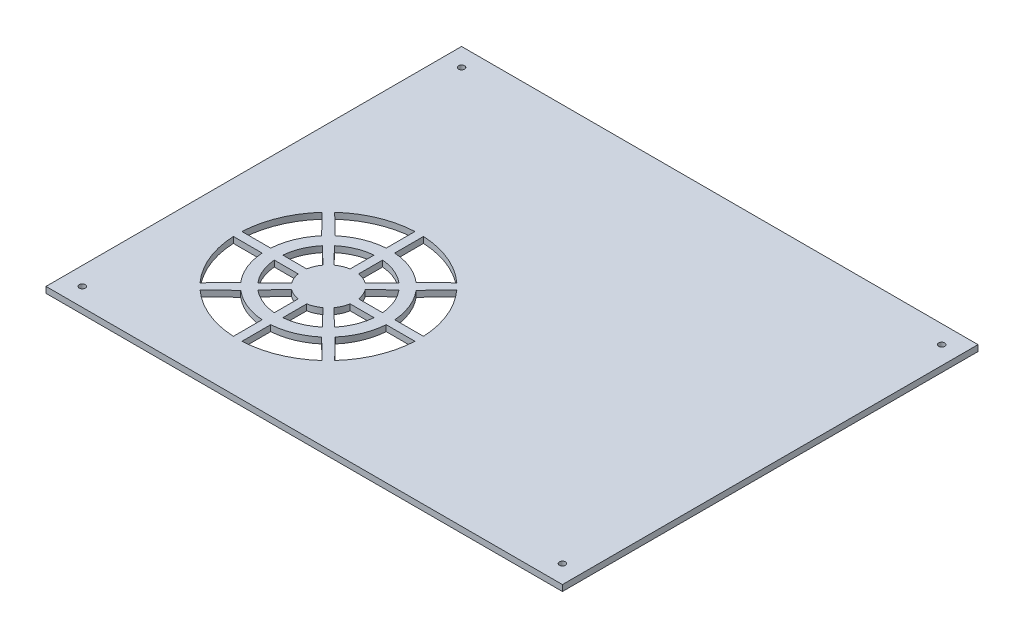
SolidWorks part; units mm, degrees
ref_plane "Front Plane" through (0, 0, 0) normal (0, 0, 1) x (1, 0, 0)
ref_plane "Top Plane" through (0, 0, 0) normal (0, 1, 0) x (1, 0, 0)
ref_plane "Right Plane" through (0, 0, 0) normal (1, 0, 0) x (0, 0, -1)
sketch "Sketch1" plane through (0, 0, 0) normal (0, 1, 0) x (1, 0, 0)
  line L1 (-128, 103) -> (128, 103)
  line L2 (-128, 103) -> (-128, -103)
  line L3 (-128, -103) -> (128, -103)
  line L4 (128, 103) -> (128, -103)
  line L5 (-128, 103) -> (128, -103) construction
  line L6 (-128, -103) -> (128, 103) construction
  point P0 (0, 0)
  dimension "D1" = 206
  dimension "D2" = 256
extrude "Boss-Extrude1" add sketch "Sketch1" along normal blind 3
sketch "Sketch2" plane through (0, 3, 0) normal (0, 1, 0) x (1, 0, 0)
  line L0 (-128, 103) -> (-128, -103) construction
  line L1 (128, 103) -> (-128, 103) construction
  line L2 (0, 0) -> (0, -86.5334) construction
  line L3 (0, 0) -> (-95.8351, 0) construction
  circle A0 centre (-119, 94) radius 1.5
  circle A1 centre (119, 94) radius 1.5
  circle A2 centre (119, -94) radius 1.5
  circle A3 centre (-119, -94) radius 1.5
  dimension "D1" = 3
  dimension "D2" = 9
  dimension "D3" = 9
extrude "Cut-Extrude3" cut sketch "Sketch2" against normal blind 4
sketch "Sketch5" plane through (0, 3, 0) normal (0, 1, 0) x (1, 0, 0)
  line L0 (-128, 103) -> (-128, -103) construction
  line L1 (-128, -103) -> (128, -103) construction
  line L3 (-105.6588, -33) -> (-105.5816, -33) construction
  line L7 (-45.133, -35.1221) -> (-33.2705, -35.1221)
  line L8 (-47.5271, -40.7706) -> (-39.0127, -48.9854)
  line L9 (-34.5756, -53.0399) -> (-24.6408, -63.2793)
  line L10 (-27.2463, -35.1221) -> (-12.9981, -35.1221)
  line L11 (-37.9601, -56.4244) -> (-27.7207, -66.3592)
  line L12 (-55.8779, -63.7537) -> (-55.8779, -78.0019)
  line L13 (-55.8779, -45.867) -> (-55.8779, -57.7295)
  line L14 (-50.2294, -43.4729) -> (-42.0146, -51.9873)
  line L15 (-55.8779, -2.2463) -> (-55.8779, 12.0019)
  line L16 (-37.9601, -9.5756) -> (-27.7207, 0.3592)
  line L17 (-55.8779, -20.133) -> (-55.8779, -8.2705)
  line L18 (-50.2294, -22.5271) -> (-42.0146, -14.0127)
  line L19 (-34.5756, -12.9601) -> (-24.6408, -2.7207)
  line L20 (-27.2463, -30.8779) -> (-12.9981, -30.8779)
  line L21 (-45.133, -30.8779) -> (-33.2705, -30.8779)
  line L22 (-47.5271, -25.2294) -> (-39.0127, -17.0146)
  line L23 (-60.1221, -45.867) -> (-60.1221, -57.7295)
  line L24 (-65.7706, -43.4729) -> (-73.9854, -51.9873)
  line L25 (-60.1221, -63.7537) -> (-60.1221, -78.0019)
  line L26 (-78.0399, -56.4244) -> (-88.2793, -66.3592)
  line L27 (-81.4244, -53.0399) -> (-91.3592, -63.2793)
  line L28 (-88.7537, -35.1221) -> (-103.0019, -35.1221)
  line L29 (-70.867, -35.1221) -> (-82.7295, -35.1221)
  line L30 (-68.4729, -40.7706) -> (-76.9873, -48.9854)
  line L31 (-88.7537, -30.8779) -> (-103.0019, -30.8779)
  line L32 (-81.4244, -12.9601) -> (-91.3592, -2.7207)
  line L33 (-70.867, -30.8779) -> (-82.7295, -30.8779)
  line L34 (-68.4729, -25.2294) -> (-76.9873, -17.0146)
  line L35 (-65.7706, -22.5271) -> (-73.9854, -14.0127)
  line L36 (-60.1221, -20.133) -> (-60.1221, -8.2705)
  line L37 (-78.0399, -9.5756) -> (-88.2793, 0.3592)
  line L38 (-60.1221, -2.2463) -> (-60.1221, 12.0019)
  arc A0 (-45.133, -35.1221) -> (-47.5271, -40.7706) centre (-58, -33) cw
  arc A1 (-33.2705, -35.1221) -> (-39.0127, -48.9854) centre (-58, -33) cw
  arc A2 (-27.2463, -35.1221) -> (-34.5756, -53.0399) centre (-58, -33) cw
  arc A3 (-12.9981, -35.1221) -> (-24.6408, -63.2793) centre (-58, -33) cw
  arc A4 (-55.8779, -63.7537) -> (-37.9601, -56.4244) centre (-58, -33) ccw
  arc A5 (-55.8779, -78.0019) -> (-27.7207, -66.3592) centre (-58, -33) ccw
  arc A6 (-55.8779, -45.867) -> (-50.2294, -43.4729) centre (-58, -33) ccw
  arc A7 (-55.8779, -57.7295) -> (-42.0146, -51.9873) centre (-58, -33) ccw
  arc A8 (-55.8779, 12.0019) -> (-27.7207, 0.3592) centre (-58, -33) cw
  arc A9 (-55.8779, -2.2463) -> (-37.9601, -9.5756) centre (-58, -33) cw
  arc A10 (-55.8779, -8.2705) -> (-42.0146, -14.0127) centre (-58, -33) cw
  arc A11 (-55.8779, -20.133) -> (-50.2294, -22.5271) centre (-58, -33) cw
  arc A12 (-27.2463, -30.8779) -> (-34.5756, -12.9601) centre (-58, -33) ccw
  arc A13 (-12.9981, -30.8779) -> (-24.6408, -2.7207) centre (-58, -33) ccw
  arc A14 (-45.133, -30.8779) -> (-47.5271, -25.2294) centre (-58, -33) ccw
  arc A15 (-33.2705, -30.8779) -> (-39.0127, -17.0146) centre (-58, -33) ccw
  arc A16 (-60.1221, -57.7295) -> (-73.9854, -51.9873) centre (-58, -33) cw
  arc A17 (-60.1221, -45.867) -> (-65.7706, -43.4729) centre (-58, -33) cw
  arc A18 (-60.1221, -78.0019) -> (-88.2793, -66.3592) centre (-58, -33) cw
  arc A19 (-60.1221, -63.7537) -> (-78.0399, -56.4244) centre (-58, -33) cw
  arc A20 (-88.7537, -35.1221) -> (-81.4244, -53.0399) centre (-58, -33) ccw
  arc A21 (-103.0019, -35.1221) -> (-91.3592, -63.2793) centre (-58, -33) ccw
  arc A22 (-70.867, -35.1221) -> (-68.4729, -40.7706) centre (-58, -33) ccw
  arc A23 (-82.7295, -35.1221) -> (-76.9873, -48.9854) centre (-58, -33) ccw
  arc A24 (-103.0019, -30.8779) -> (-91.3592, -2.7207) centre (-58, -33) cw
  arc A25 (-88.7537, -30.8779) -> (-81.4244, -12.9601) centre (-58, -33) cw
  arc A26 (-82.7295, -30.8779) -> (-76.9873, -17.0146) centre (-58, -33) cw
  arc A27 (-70.867, -30.8779) -> (-68.4729, -25.2294) centre (-58, -33) cw
  arc A28 (-60.1221, -20.133) -> (-65.7706, -22.5271) centre (-58, -33) ccw
  arc A29 (-60.1221, -8.2705) -> (-73.9854, -14.0127) centre (-58, -33) ccw
  arc A30 (-60.1221, -2.2463) -> (-78.0399, -9.5756) centre (-58, -33) ccw
  arc A31 (-60.1221, 12.0019) -> (-88.2793, 0.3592) centre (-58, -33) ccw
  point P0 (-58, -33)
  dimension "D1" = 70
  dimension "70" = 70
extrude "Cut-Extrude6" cut sketch "Sketch5" against normal blind 4
